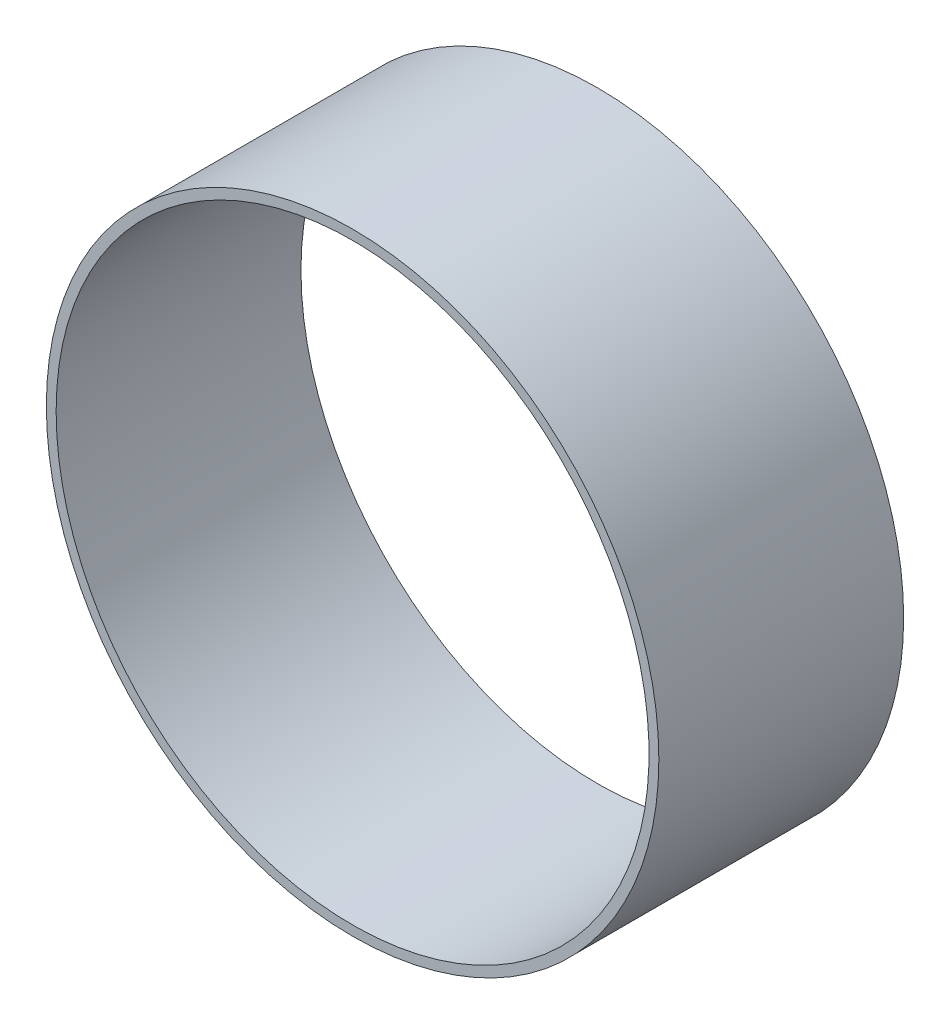
SolidWorks part; units mm, degrees
ref_plane "Front Plane" through (0, 0, 0) normal (0, 0, 1) x (1, 0, 0)
ref_plane "Top Plane" through (0, 0, 0) normal (0, 1, 0) x (1, 0, 0)
ref_plane "Right Plane" through (0, 0, 0) normal (1, 0, 0) x (0, 0, -1)
ref_plane "Plane_axle_y" through (0, -19.05, 0) normal (0, 1, 0) x (1, 0, 0)
sketch "Sk_insert_section" plane through (0, -19.05, 0) normal (0, 1, 0) x (1, 0, 0)
  line L0 (76.9302, 15.875) -> (78.2002, 15.875)
  line L1 (78.2002, 15.875) -> (78.2002, -15.875)
  line L2 (78.2002, -15.875) -> (76.9302, -15.875)
  line L3 (76.9302, -15.875) -> (76.9302, 15.875)
  line L4 (38.481, 50.8) -> (38.481, -50.8) construction
revolve "Rev_insert" add sketch "Sk_insert_section" angle 360 about L4
